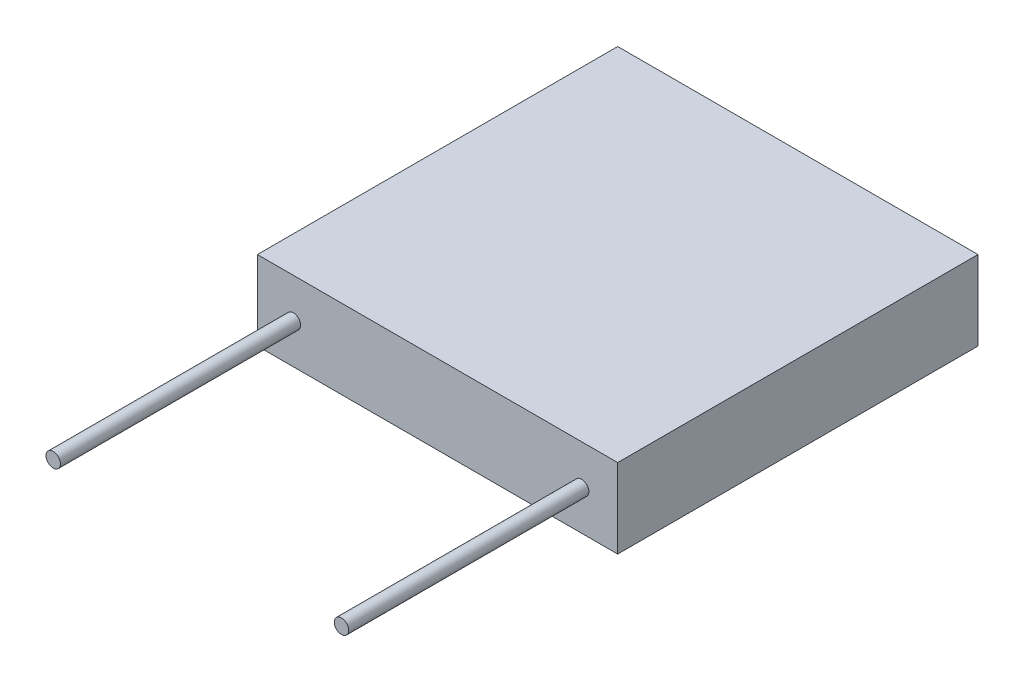
SolidWorks part; units mm, degrees
ref_plane "前视基准面" through (0, 0, 0) normal (0, 0, 1) x (1, 0, 0)
ref_plane "上视基准面" through (0, 0, 0) normal (0, 1, 0) x (1, 0, 0)
ref_plane "右视基准面" through (0, 0, 0) normal (1, 0, 0) x (0, 0, -1)
sketch "草图1" plane through (0, 0, 0) normal (0, 1, 0) x (1, 0, 0)
  line L0 (-59.7364, 0) -> (83.9948, 0) construction
  line L1 (-7.5, 7.5) -> (7.5, 7.5)
  line L2 (-7.5, 7.5) -> (-7.5, -7.5)
  line L3 (-7.5, -7.5) -> (7.5, -7.5)
  line L4 (7.5, 7.5) -> (7.5, -7.5)
  line L5 (0, 52.7621) -> (0, -60.9493) construction
  dimension "D1" = 15
  dimension "D2" = 15
extrude "拉伸1" add sketch "草图1" along normal blind 3.3
sketch "草图2" plane through (0, 0, 7.5) normal (0, 0, 1) x (1, 0, 0)
  line L0 (-9.3144, 1.65) -> (9.8458, 1.65) construction
  line L1 (-7.5, 3.3) -> (7.5, 3.3) construction
  line L2 (-7.5, 0) -> (7.5, 0) construction
  line L3 (0, 5.0008) -> (0, -4.2198) construction
  line L4 (-6, 3.3543) -> (-6, -1.6197) construction
  circle A0 centre (-6, 1.65) radius 0.3
  circle A1 centre (6, 1.65) radius 0.3
  dimension "D2" = 0.6
  dimension "D1" = 6
extrude "拉伸2" add sketch "草图2" along normal blind 10
